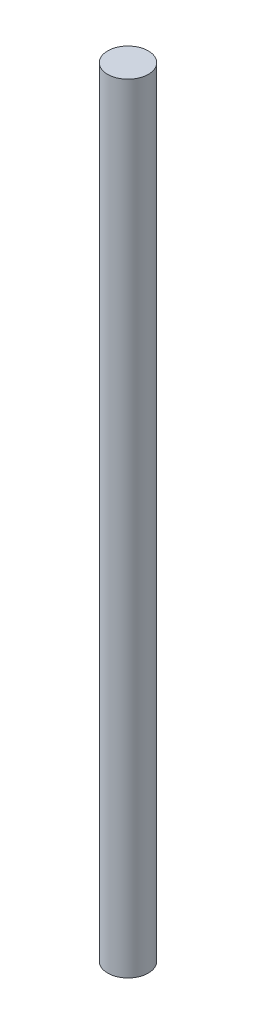
SolidWorks part; units mm, degrees
ref_plane "Front Plane" through (0, 0, 0) normal (0, 0, 1) x (1, 0, 0)
ref_plane "Top Plane" through (0, 0, 0) normal (0, 1, 0) x (1, 0, 0)
ref_plane "Right Plane" through (0, 0, 0) normal (1, 0, 0) x (0, 0, -1)
sketch "Sketch1" plane through (0, 0, 0) normal (0, 1, 0) x (1, 0, 0)
  circle A0 centre (0, 0) radius 6.35
  dimension "D1" = 12.7
extrude "Boss-Extrude1" add sketch "Sketch1" along normal mid plane 243
